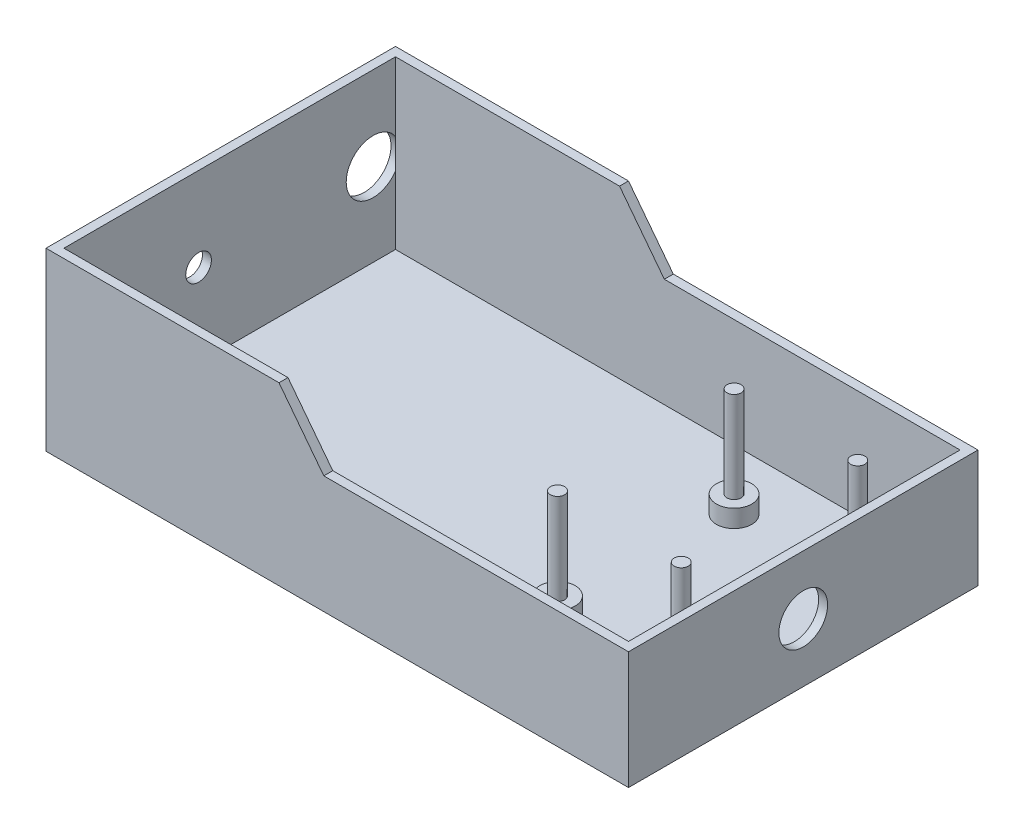
SolidWorks part; units mm, degrees
ref_plane "Front Plane" through (0, 0, 0) normal (0, 0, 1) x (1, 0, 0)
ref_plane "Top Plane" through (0, 0, 0) normal (0, 1, 0) x (1, 0, 0)
ref_plane "Right Plane" through (0, 0, 0) normal (1, 0, 0) x (0, 0, -1)
sketch "Sketch1" plane through (0, 0, 0) normal (0, 0, 1) x (1, 0, 0)
  line L0 (0, 0) -> (152.4, 0)
  line L1 (152.4, 0) -> (152.4, 26.9875)
  line L2 (152.4, 26.9875) -> (76.2, 26.9875)
  line L3 (0, 0) -> (0, 43.4975)
  line L4 (0, 43.4975) -> (63.5, 43.4975)
  line L5 (63.5, 43.4975) -> (76.2, 26.9875)
  dimension "D1" = 152.4
  dimension "D2" = 26.9875
  dimension "D3" = 76.2
  dimension "D4" = 43.4975
  dimension "D5" = 63.5
extrude "Boss-Extrude1" add sketch "Sketch1" along normal blind 2.54
sketch "Sketch2" plane through (0, 0, 0) normal (0, -1, 0) x (-1, 0, 0)
  line L0 (-152.4, -2.54) -> (-152.4, -96.52)
  line L1 (-152.4, -96.52) -> (0, -96.52)
  line L2 (0, -96.52) -> (0, -2.54)
  line L3 (-152.4, -2.54) -> (0, -2.54)
  dimension "D1" = 93.98
  dimension "D2" = 152.4
extrude "Boss-Extrude2" add sketch "Sketch2" along normal blind 2.54 separate body
sketch "Sketch3" plane through (0, 0, 96.52) normal (0, 0, 1) x (1, 0, 0)
  line L0 (0, 0) -> (0, 43.4975)
  line L1 (0, 43.4975) -> (63.5, 43.4975)
  line L2 (63.5, 43.4975) -> (76.2, 26.9875)
  line L3 (76.2, 26.9875) -> (152.4, 26.9875)
  line L4 (152.4, 26.9875) -> (152.4, -2.54)
  line L5 (152.4, -2.54) -> (0, -2.54)
  line L6 (0, -2.54) -> (0, 0)
extrude "Boss-Extrude3" add sketch "Sketch3" along normal blind 2.54
sketch "Sketch4" plane through (0, 0, 2.54) normal (0, 0, -1) x (-1, 0, 0)
  line L1 (-152.4, 0) -> (0, 0)
  line L2 (-152.4, 0) -> (-152.4, -2.54)
  line L3 (-152.4, -2.54) -> (0, -2.54)
  line L4 (0, 0) -> (0, -2.54)
extrude "Boss-Extrude4" add sketch "Sketch4" along normal blind 2.54
sketch "Sketch10" plane through (0, 0, 0) normal (0, 0, -1) x (-1, 0, 0)
  line L0 (0, 43.4975) -> (0, 47.3075)
  line L1 (0, 47.3075) -> (-63.5, 47.3075)
  line L2 (-152.4, 26.9875) -> (-152.4, 30.7975)
  line L3 (-152.4, 30.7975) -> (-76.2, 30.7975)
  line L4 (-76.2, 30.7975) -> (-63.5, 47.3075)
  line L11 (0, -2.54) -> (0, 43.4975)
  line L12 (0, 43.4975) -> (-63.5, 43.4975)
  line L13 (-63.5, 43.4975) -> (-76.2, 26.9875)
  line L14 (-76.2, 26.9875) -> (-152.4, 26.9875)
  line L15 (-152.4, 26.9875) -> (-152.4, -2.54)
  line L16 (-152.4, -2.54) -> (0, -2.54)
  line L18 (0, 43.4975) -> (-63.5, 43.4975)
  line L19 (-63.5, 43.4975) -> (-76.2, 26.9875)
  line L20 (-76.2, 26.9875) -> (-152.4, 26.9875)
  dimension "D1" = 3.81
  dimension "D2" = 3.81
  dimension "D3" = 76.2
  dimension "D4" = 0
extrude "Boss-Extrude13" add sketch "Sketch10" against normal blind 2.54
sketch "Sketch18" plane through (0, 0, 99.06) normal (0, 0, 1) x (1, 0, 0)
  line L0 (0, 43.4975) -> (0, 47.3075)
  line L1 (0, 47.3075) -> (63.5, 47.3075)
  line L2 (63.5, 47.3075) -> (76.2, 30.7975)
  line L3 (76.2, 30.7975) -> (152.4, 30.7975)
  line L4 (152.4, 30.7975) -> (152.4, 26.9875)
  line L5 (152.4, 26.9875) -> (76.2, 26.9875)
  line L6 (76.2, 26.9875) -> (63.5, 43.4975)
  line L7 (63.5, 43.4975) -> (0, 43.4975)
extrude "Boss-Extrude14" add sketch "Sketch18" against normal blind 2.54
sketch "Sketch19" plane through (0, 0, 99.06) normal (0, 0, 1) x (1, 0, 0)
  line L0 (0, -2.54) -> (152.4, -2.54)
  line L2 (152.4, 30.7975) -> (160.02, 30.7975)
  line L3 (152.4, 30.7975) -> (152.4, -2.54)
  line L4 (152.4, -2.54) -> (160.02, -2.54)
  line L5 (160.02, 30.7975) -> (160.02, -2.54)
  line M5 (152.4, -2.54) -> (152.4, 30.7975)
  dimension "D1" = 7.62
extrude "Boss-Extrude15" add sketch "Sketch19" against normal blind 2.54 contours L5 L2 L4 M5
sketch "Sketch20" plane through (0, 0, 0) normal (0, 0, -1) x (-1, 0, 0)
  line L1 (-152.4, 30.7975) -> (-160.02, 30.7975)
  line L2 (-152.4, 30.7975) -> (-152.4, -2.54)
  line L3 (-152.4, -2.54) -> (-160.02, -2.54)
  line L4 (-160.02, 30.7975) -> (-160.02, -2.54)
extrude "Boss-Extrude16" add sketch "Sketch20" against normal blind 2.54
sketch "Sketch21" plane through (152.4, 0, 0) normal (1, 0, 0) x (0, 0, -1)
  line L1 (-96.52, 0) -> (-2.54, 0)
  line L2 (-96.52, 0) -> (-96.52, -2.54)
  line L3 (-96.52, -2.54) -> (-2.54, -2.54)
  line L4 (-2.54, 0) -> (-2.54, -2.54)
extrude "Boss-Extrude17" add sketch "Sketch21" along normal blind 7.62
sketch "Sketch22" plane through (0, 0, 99.06) normal (0, 0, 1) x (1, 0, 0)
  line L0 (0, -2.54) -> (160.02, -2.54)
  line L2 (160.02, 30.7975) -> (162.56, 30.7975)
  line L3 (160.02, 30.7975) -> (160.02, -2.54)
  line L4 (160.02, -2.54) -> (162.56, -2.54)
  line L5 (162.56, 30.7975) -> (162.56, -2.54)
  dimension "D1" = 2.54
extrude "Boss-Extrude18" add sketch "Sketch22" against normal blind 99.06 contours L4 L5 L2 L3
sketch "Sketch23" plane through (0, 0, 0) normal (-1, 0, 0) x (0, 0, 1)
  line L1 (0, 47.3075) -> (99.06, 47.3075)
  line L2 (0, 47.3075) -> (0, -2.54)
  line L3 (0, -2.54) -> (99.06, -2.54)
  line L4 (99.06, 47.3075) -> (99.06, -2.54)
extrude "Boss-Extrude19" add sketch "Sketch23" along normal blind 2.54
sketch "Sketch24" plane through (-2.54, 0, 0) normal (-1, 0, 0) x (0, 0, 1)
  line L0 (0, -2.54) -> (0, 47.3075)
  line L1 (0, 47.3075) -> (0, 23.5185)
  line L2 (0, -2.54) -> (8.89, -2.54)
  line L3 (0, -2.54) -> (99.06, -2.54) construction
  circle A0 centre (8.89, 23.5185) radius 7.62
  circle A1 centre (78.9061, 23.5185) radius 3.2856
  circle A2 centre (58.3587, 23.5185) radius 3.6393
  dimension "D2" = 15.24
  dimension "D1" = 8.89
extrude "Cut-Extrude2" cut sketch "Sketch24" against normal blind 2.54 contours A2 | A0 | A1
sketch "Sketch25" plane through (162.56, 0, 0) normal (1, 0, 0) x (0, 0, -1)
  line L0 (-99.06, 30.7975) -> (-99.06, 14.1287)
  line L1 (-99.06, 30.7975) -> (-99.06, -2.54) construction
  line L2 (-99.06, 14.1287) -> (-49.53, 14.1287)
  circle A0 centre (-49.53, 14.1287) radius 6.9069
  dimension "D1" = 49.53
extrude "Cut-Extrude3" cut sketch "Sketch25" against normal blind 2.54
sketch "Sketch26" plane through (0, 0, 99.06) normal (0, 0, 1) x (1, 0, 0)
  line L0 (162.56, -2.54) -> (101.6, -2.54)
  line L1 (-2.54, -2.54) -> (162.56, -2.54) construction
  circle A0 centre (101.6, 20.7951) radius 6.35
  dimension "D2" = 12.7
  dimension "D1" = 60.96
sketch "Sketch27" plane through (0, 47.3075, 0) normal (0, 1, 0) x (1, 0, 0)
  line L1 (-2.54, -98.1101) -> (-2.54, -99.06)
sketch "Sketch28" plane through (0, 0, 99.06) normal (0, 0, 1) x (1, 0, 0)
  line L0 (63.5, 47.3075) -> (63.5, 30.0904)
  line L1 (63.5, 30.0904) -> (76.2464, 30.0904)
  line L2 (76.2464, 30.0904) -> (76.2, 30.7975)
  line L3 (76.2, 30.7975) -> (63.5, 31.0105)
  line L4 (63.5, 31.0105) -> (63.5, 47.3075)
  line L5 (76.2, 30.7975) -> (162.56, 30.7975)
sketch "Sketch29" plane through (0, 0, 0) normal (0, 1, 0) x (1, 0, 0)
  line L0 (0, 0) -> (0, -99.06) construction
  line L1 (-2.54, -99.06) -> (162.56, -99.06) construction
  line L2 (0, -2.5402) -> (159.5726, -2.5402)
  line L3 (160.02, -2.54) -> (160.02, -96.52) construction
  circle A0 centre (112.968, -19.5402) radius 2
  circle A1 centre (148.02, -19.5402) radius 2
  circle A2 centre (148.02, -69.5782) radius 2
  circle A3 centre (112.968, -69.5782) radius 2
  dimension "D1" = 12
  dimension "D2" = 17
  dimension "D3" = 4
  dimension "D4" = 2
  dimension "D5" = 2
extrude "Boss-Extrude20" add sketch "Sketch29" along normal up to surface (30.7975 mm away) contours A0 | A1 | A3 | A2 up to face at (118.745, 30.7975, 49.53)
sketch "Sketch31" plane through (0, 0, 0) normal (0, 1, 0) x (1, 0, 0)
  circle A0 centre (112.968, -19.5402) radius 5
  circle A1 centre (148.02, -19.5402) radius 5
  circle A2 centre (112.968, -69.5782) radius 5
  circle A3 centre (148.02, -69.5782) radius 5
  dimension "D1" = 10
extrude "Boss-Extrude21" add sketch "Sketch31" along normal blind 5
